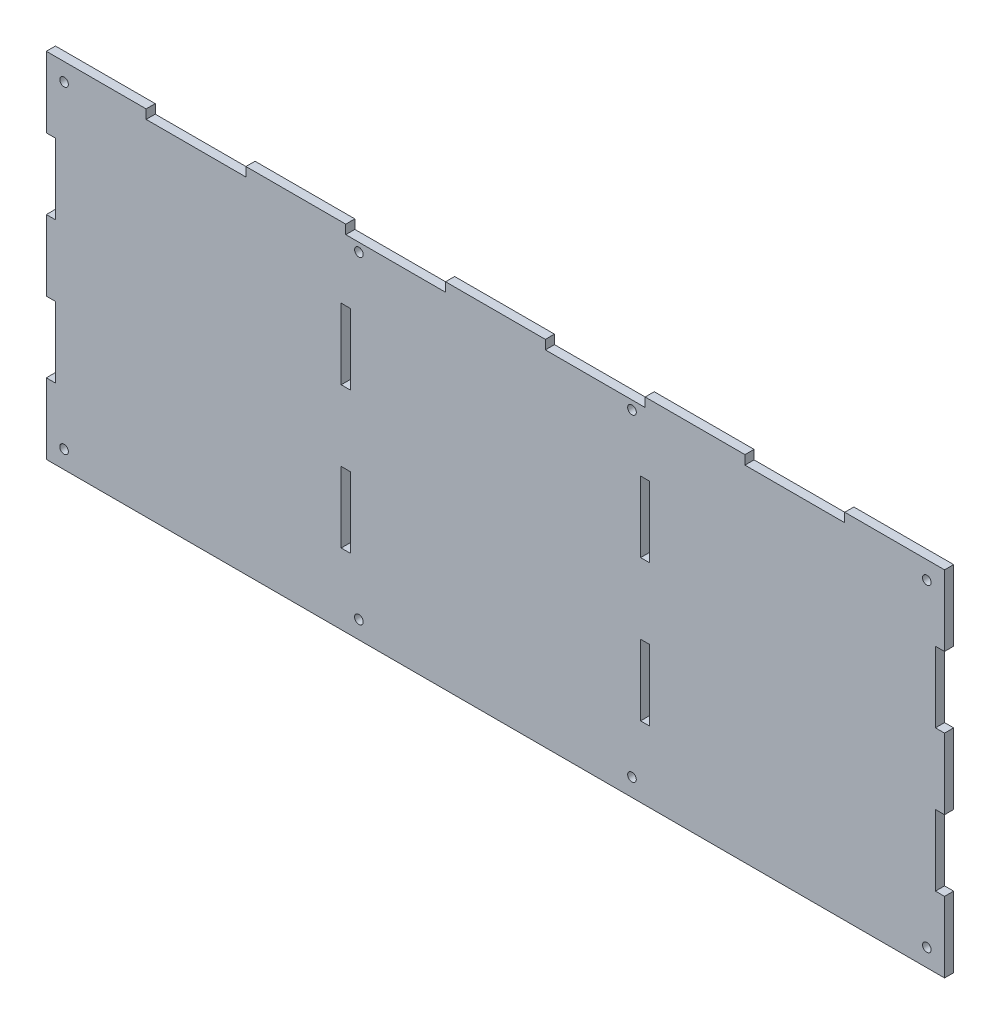
SolidWorks part; units mm, degrees
ref_plane "Front Plane" through (0, 0, 0) normal (0, 0, 1) x (1, 0, 0)
ref_plane "Top Plane" through (0, 0, 0) normal (0, 1, 0) x (1, 0, 0)
ref_plane "Right Plane" through (0, 0, 0) normal (1, 0, 0) x (0, 0, -1)
sketch "Sketch1" plane through (0, 0, 0) normal (0, 0, 1) x (1, 0, 0)
  line L0 (0, 120) -> (313, 120) construction
  line L1 (0, 0) -> (313, 0)
  line L2 (0, 0) -> (0, 123.175) construction
  line L4 (313, 0) -> (313, 123.175) construction
  line L22 (0, 123.175) -> (34.7778, 123.175)
  line L23 (34.7778, 123.175) -> (34.7778, 120)
  line L24 (34.7778, 120) -> (69.5556, 120)
  line L25 (69.5556, 120) -> (69.5556, 123.175)
  line L26 (69.5556, 123.175) -> (104.3333, 123.175)
  line L27 (104.3333, 123.175) -> (104.3333, 120)
  line L28 (104.3333, 120) -> (139.1111, 120)
  line L29 (139.1111, 120) -> (139.1111, 123.175)
  line L30 (139.1111, 123.175) -> (173.8889, 123.175)
  line L31 (173.8889, 123.175) -> (173.8889, 120)
  line L32 (173.8889, 120) -> (208.6667, 120)
  line L33 (208.6667, 120) -> (208.6667, 123.175)
  line L34 (208.6667, 123.175) -> (243.4444, 123.175)
  line L35 (243.4444, 123.175) -> (243.4444, 120)
  line L36 (243.4444, 120) -> (278.2222, 120)
  line L37 (278.2222, 120) -> (278.2222, 123.175)
  line L38 (278.2222, 123.175) -> (313, 123.175)
  line L39 (0, 123.175) -> (0, 98.54)
  line L44 (0, 98.54) -> (3.175, 98.54)
  line L45 (3.175, 98.54) -> (3.175, 73.905)
  line L46 (3.175, 73.905) -> (0, 73.905)
  line L47 (0, 73.905) -> (0, 49.27)
  line L48 (0, 49.27) -> (3.175, 49.27)
  line L49 (3.175, 49.27) -> (3.175, 24.635)
  line L50 (3.175, 24.635) -> (0, 24.635)
  line L51 (0, 24.635) -> (0, 0)
  line L52 (104.3333, 120) -> (104.3333, 0) construction
  line L53 (208.6667, 120) -> (208.6667, 0) construction
  line L54 (313, 123.175) -> (313, 98.54)
  line L55 (313, 98.54) -> (309.825, 98.54)
  line L56 (309.825, 98.54) -> (309.825, 73.905)
  line L57 (309.825, 73.905) -> (313, 73.905)
  line L58 (313, 73.905) -> (313, 49.27)
  line L59 (313, 49.27) -> (309.825, 49.27)
  line L60 (309.825, 49.27) -> (309.825, 24.635)
  line L61 (309.825, 24.635) -> (313, 24.635)
  line L62 (313, 24.635) -> (313, 0)
  line L63 (3.175, 98.54) -> (309.825, 98.54) construction
  line L64 (309.825, 73.905) -> (3.175, 73.905) construction
  line L65 (3.175, 49.27) -> (309.825, 49.27) construction
  line L66 (309.825, 24.635) -> (3.175, 24.635) construction
  line L67 (3.175, 120) -> (3.175, 98.54) construction
  line L68 (105.9208, 98.54) -> (102.7458, 98.54)
  line L69 (105.9208, 98.54) -> (105.9208, 73.905)
  line L70 (105.9208, 73.905) -> (102.7458, 73.905)
  line L71 (102.7458, 98.54) -> (102.7458, 73.905)
  line L72 (105.9208, 49.27) -> (102.7458, 49.27)
  line L73 (105.9208, 49.27) -> (105.9208, 24.635)
  line L74 (105.9208, 24.635) -> (102.7458, 24.635)
  line L75 (102.7458, 49.27) -> (102.7458, 24.635)
  line L76 (210.2542, 98.54) -> (207.0792, 98.54)
  line L77 (210.2542, 98.54) -> (210.2542, 73.905)
  line L78 (210.2542, 73.905) -> (207.0792, 73.905)
  line L79 (207.0792, 98.54) -> (207.0792, 73.905)
  line L80 (210.2542, 49.27) -> (207.0792, 49.27)
  line L81 (210.2542, 49.27) -> (210.2542, 24.635)
  line L82 (210.2542, 24.635) -> (207.0792, 24.635)
  line L83 (207.0792, 49.27) -> (207.0792, 24.635)
  line L84 (3.175, 61.5875) -> (309.825, 61.5875) construction
  line L85 (3.175, 73.905) -> (3.175, 49.27) construction
  line L86 (309.825, 73.905) -> (309.825, 49.27) construction
  line L87 (156.5, 120) -> (156.5, 0) construction
  line L88 (105.9208, 120) -> (105.9208, 98.54) construction
  circle A0 centre (6.175, 117) radius 1.5
  circle A2 centre (108.9208, 117) radius 1.5
  circle A3 centre (108.9208, 6.175) radius 1.5
  circle A4 centre (6.175, 6.175) radius 1.5
  circle A5 centre (306.825, 6.175) radius 1.5
  circle A6 centre (204.0792, 6.175) radius 1.5
  circle A7 centre (204.0792, 117) radius 1.5
  circle A8 centre (306.825, 117) radius 1.5
  point P45 (104.3333, 98.54)
  point P54 (208.6667, 98.54)
  dimension "D4" = 3.175
  dimension "D8" = 3
  dimension "D11" = 3
  dimension "D1" = 313
  dimension "D2" = 3.175
  dimension "D3" = 120
  dimension "D5" = 3.175
  dimension "D6" = 3.175
  dimension "D7" = 3.175
  dimension "D9" = 3
  dimension "D10" = 3
  dimension "D12" = 3
  dimension "D13" = 3
extrude "Boss-Extrude1" add sketch "Sketch1" along normal blind 3.175
